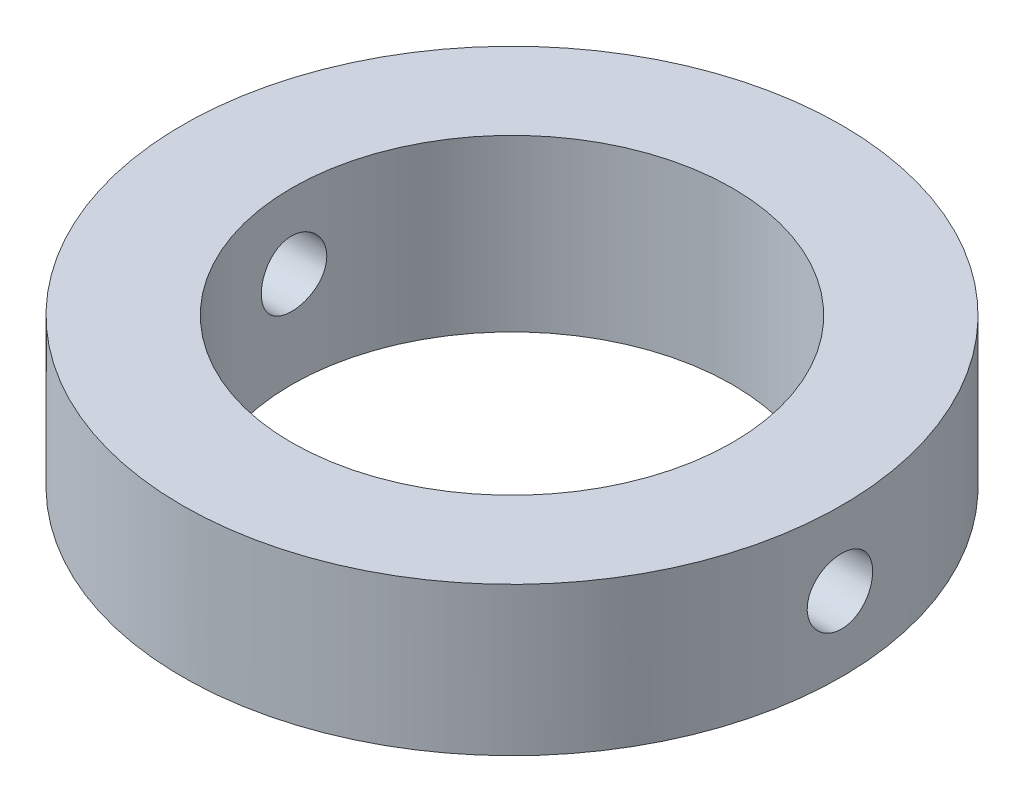
SolidWorks part; units mm, degrees
ref_plane "Front Plane" through (0, 0, 0) normal (0, 0, 1) x (1, 0, 0)
ref_plane "Top Plane" through (0, 0, 0) normal (0, 1, 0) x (1, 0, 0)
ref_plane "Right Plane" through (0, 0, 0) normal (1, 0, 0) x (0, 0, -1)
sketch "Sketch1" plane through (0, 0, 0) normal (0, 1, 0) x (1, 0, 0)
  circle A0 centre (0, 0) radius 10.1
  circle A1 centre (0, 0) radius 15.1
extrude "Boss-Extrude1" add sketch "Sketch1" along normal blind 7
sketch "Sketch2" plane through (0, 0, 0) normal (1, 0, 0) x (0, 0, -1)
  line L0 (0, 7) -> (0, 0)
  line L1 (10.1, 7) -> (-10.1, 7) construction
  line L2 (0, 0) -> (0, 3.5)
  line L3 (0, 3.5) -> (0, 4.402)
  circle A1 centre (0, 4.402) radius 1.5
extrude "Cut-Extrude3" cut sketch "Sketch2" along normal blind 22 and the other way blind 24 contours L0 A1 | L0 A1
sketch "Sketch4" plane through (0, 0, 0) normal (0, -1, 0) x (1, 0, 0)
  circle A0 centre (0, 0) radius 11.1
  circle A1 centre (0, 0) radius 23.3538
extrude "Cut-Extrude4" cut sketch "Sketch4" against normal blind 1
sketch "Sketch6" plane through (0, 7, 0) normal (0, 1, 0) x (1, 0, 0)
  circle A0 centre (0, 0) radius 10.1 construction
  circle A1 centre (0, 0) radius 15.1 construction
  circle A2 centre (0, 0) radius 10.1
  circle A3 centre (0, 0) radius 15.1
extrude "Boss-Extrude2" add sketch "Sketch6" along normal blind 0.8
